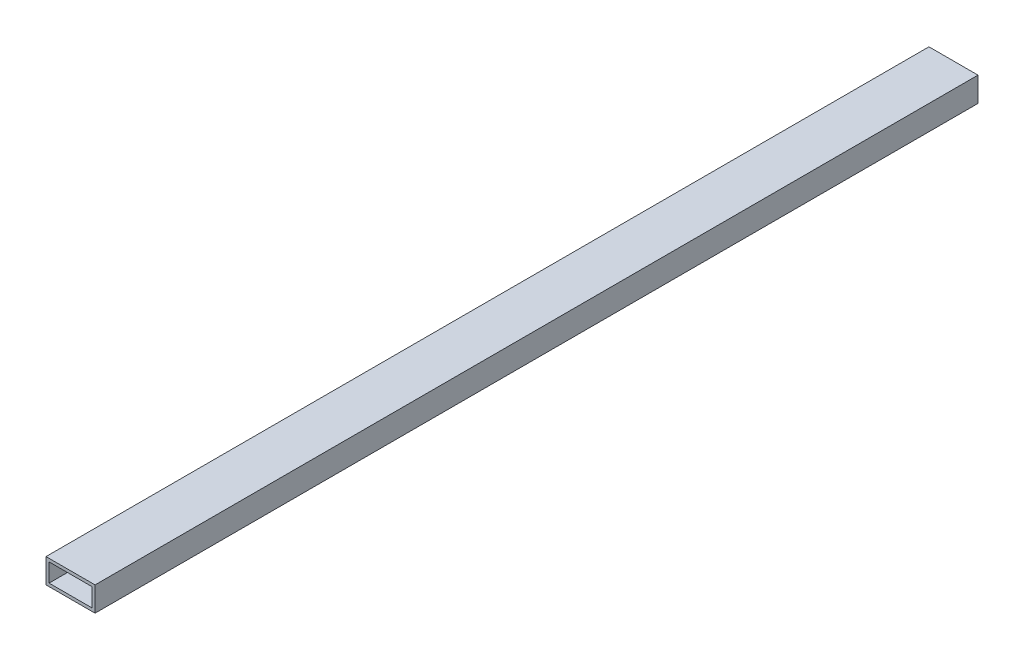
SolidWorks part; units mm, degrees
ref_plane "Front Plane" through (0, 0, 0) normal (0, 0, 1) x (1, 0, 0)
ref_plane "Top Plane" through (0, 0, 0) normal (0, 1, 0) x (1, 0, 0)
ref_plane "Right Plane" through (0, 0, 0) normal (1, 0, 0) x (0, 0, -1)
sketch "Sketch1" plane through (0, 0, 0) normal (0, 0, 1) x (1, 0, 0)
  line L1 (-25.4, 12.7) -> (25.4, 12.7)
  line L2 (-25.4, 12.7) -> (-25.4, -12.7)
  line L3 (-25.4, -12.7) -> (25.4, -12.7)
  line L4 (25.4, 12.7) -> (25.4, -12.7)
  line L5 (-25.4, 12.7) -> (25.4, -12.7) construction
  line L6 (-25.4, -12.7) -> (25.4, 12.7) construction
  point P0 (0, 0)
  dimension "D1" = 50.8
  dimension "D2" = 25.4
extrude "Boss-Extrude1" add sketch "Sketch1" along normal blind 914.4
shell "Shell1" thickness 3.175
